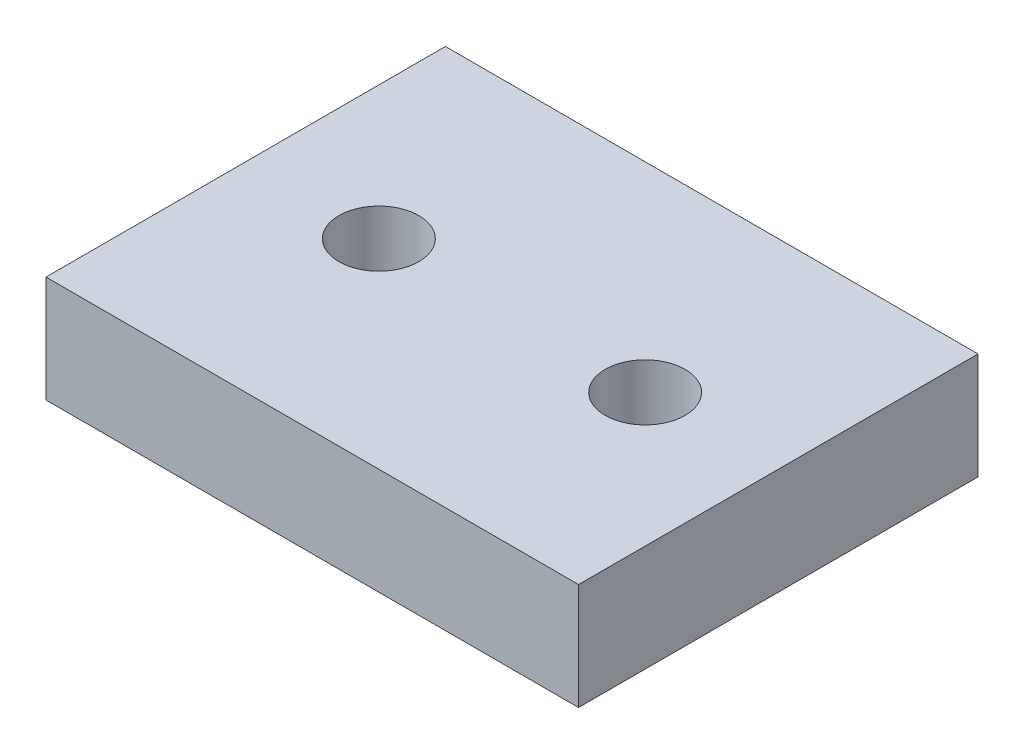
SolidWorks part; units mm, degrees
ref_plane "Front Plane" through (0, 0, 0) normal (0, 0, 1) x (1, 0, 0)
ref_plane "Top Plane" through (0, 0, 0) normal (0, 1, 0) x (1, 0, 0)
ref_plane "Right Plane" through (0, 0, 0) normal (1, 0, 0) x (0, 0, -1)
sketch "Sketch2" plane through (0, 0, 0) normal (1, 0, 0) x (0, 0, -1)
  line L0 (0, 0) -> (15, 0)
  line L4 (15, 4) -> (0, 4)
  line L7 (0, 4) -> (0, 0)
  line L8 (15, 0) -> (15, 4)
  dimension "D2" = 4
  dimension "D3" = 15
extrude "ProfileBoss-Extrude1" add sketch "Sketch2" along normal blind 20
sketch "MountHolesSketch5" plane through (0, 4, 0) normal (0, 1, 0) x (1, 0, 0)
  line L0 (0, 15) -> (0, 0) construction
  line L1 (20, 15) -> (20, 0) construction
  line L3 (20, 0) -> (0, 0) construction
  circle A0 centre (5, 7.5) radius 1.5
  circle A1 centre (15, 7.5) radius 1.5
  dimension "D1" = 3
  dimension "D2" = 5
  dimension "D4" = 7.5
  dimension "D3" = 5
extrude "MountHolesCut-Extrude2" cut sketch "MountHolesSketch5" against normal through all
equation "\"ChannelRiserHeight\"= 4mm"
equation "\"D2@Sketch2\"=\"ChannelRiserHeight\""
equation "\"ChannelWidth\"= 15mm"
equation "\"ChannelLength\"= 20mm"
equation "\"D1@ProfileBoss-Extrude1\"=\"ChannelLength\""
equation "\"D3@Sketch2\"=\"ChannelWidth\""
equation "\"D4@MountHolesSketch5\"=\"ChannelWidth\"/2"
equation "\"D2@MountHolesSketch5\"=\"ChannelLength\"/4"
equation "\"D3@MountHolesSketch5\"=\"ChannelLength\"/4"
